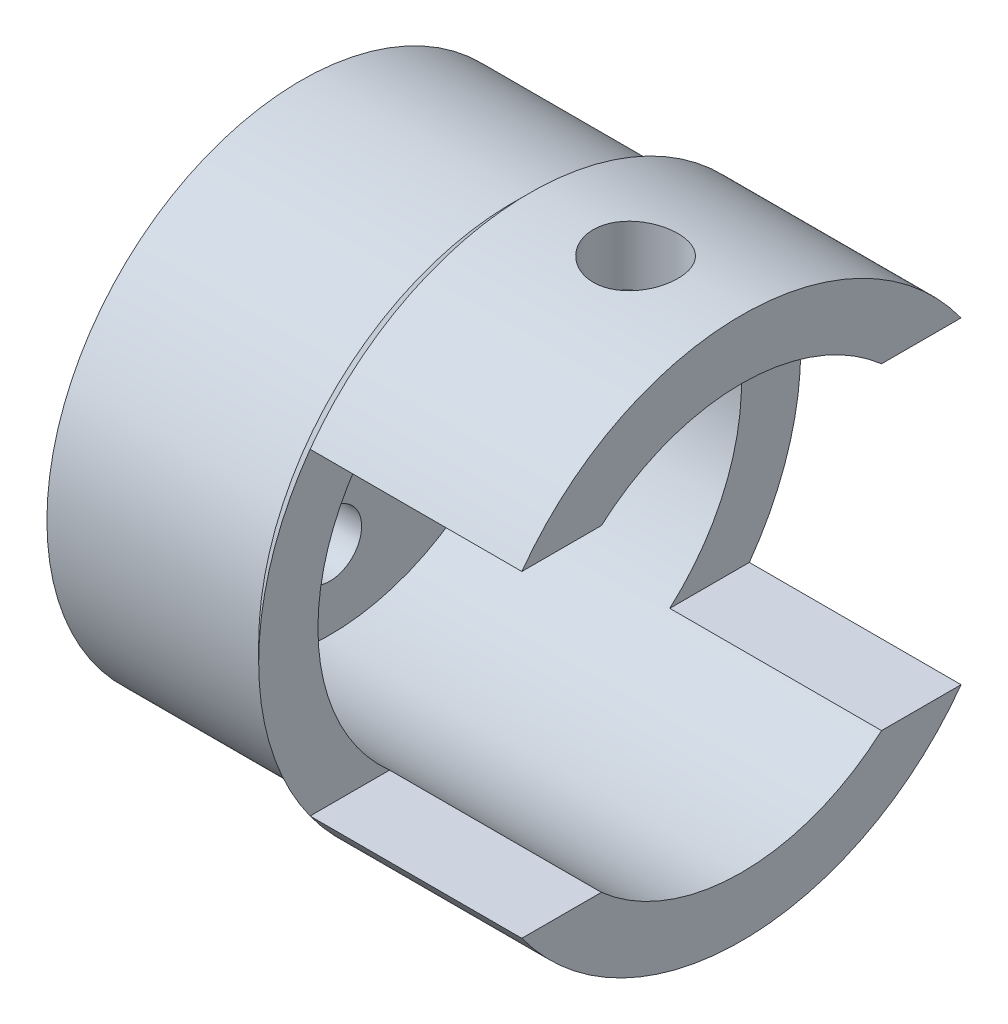
SolidWorks part; units mm, degrees
ref_plane "Plan de face" through (0, 0, 0) normal (0, 0, 1) x (1, 0, 0)
ref_plane "Plan de dessus" through (0, 0, 0) normal (0, 1, 0) x (1, 0, 0)
ref_plane "Plan de droite" through (0, 0, 0) normal (1, 0, 0) x (0, 0, -1)
sketch "Esquisse1" plane through (0, 0, 0) normal (0, 0, 1) x (1, 0, 0)
  line L0 (0, 0) -> (19.5537, 0) construction
  line L1 (0, 12) -> (10, 12)
  line L2 (10, 12) -> (10.7985, 12.7985)
  line L3 (10.7985, 12.7985) -> (20.7985, 12.7985)
  line L7 (0, 12) -> (0, 10)
  line L11 (20.7985, 12.7985) -> (20.7985, 10.7985)
  line L12 (0, 10) -> (0, 0)
  line L13 (0, 0) -> (1.3608, 0)
  line L14 (1.3608, 0) -> (1.3608, 10)
  line L15 (12.2426, 10) -> (1.3608, 10)
  line L16 (12.2426, 10) -> (20.7985, 10)
  line L17 (20.7985, 10) -> (20.7985, 10.7985)
  dimension "D1" = 2
  dimension "D2" = 10
  dimension "D3" = 10
  dimension "D5" = 2
revolve "Révolution1" add sketch "Esquisse1" angle 360 about L0
sketch "Esquisse2" plane through (0, 0, 0) normal (-1, 0, 0) x (0, 0, 1)
  circle A0 centre (0, 0) radius 2.5
  circle A1 centre (0, 6.3) radius 1.5
  circle A2 centre (6.3, 0) radius 1.5
  circle A3 centre (0, -6.3) radius 1.5
  circle A4 centre (-6.3, 0) radius 1.5
  dimension "D1" = 5
  dimension "D2" = 3
  dimension "D3" = 3
  dimension "D4" = 3
  dimension "D5" = 3
  dimension "D6" = 6.3
  dimension "D7" = 6.3
  dimension "D8" = 6.3
  dimension "D9" = 6.3
extrude "Enlèv. mat.-Extru.1" cut sketch "Esquisse2" against normal up to next
sketch "Esquisse3" plane through (0, 0, 0) normal (-1, 0, 0) x (0, 0, 1)
  line L0 (0, -6.3) -> (0, 6.3) construction
ref_plane "Plan1" through (0, 0, 0) normal (0, 0, -1) x (0, 1, 0)
sketch "Esquisse4" plane through (0, 0, 0) normal (0, 0, -1) x (0, 1, 0)
  line L0 (12.7985, 20.7985) -> (-12.7985, 20.7985) construction
  line L1 (7.5015, 20.7985) -> (-7.4985, 20.7985)
  line L2 (7.5015, 20.7985) -> (7.5015, 10.7985)
  line L3 (7.5015, 10.7985) -> (-7.4985, 10.7985)
  line L4 (-7.4985, 20.7985) -> (-7.4985, 10.7985)
  line L5 (12.7985, 10.7985) -> (-12.7985, 10.7985) construction
  line L7 (-12.7985, 20.7985) -> (-12.7985, 10.7985) construction
  dimension "D1" = 15
  dimension "D2" = 5.3
extrude "Enlèv. mat.-Extru.2" cut sketch "Esquisse4" against normal through all both and the other way through all
ref_plane "Plan2" through (0, 12.7985, 0) normal (0, 1, 0) x (1, 0, 0)
sketch "Esquisse5" plane through (0, 12.7985, 0) normal (0, 1, 0) x (1, 0, 0)
  line L0 (20.7985, -10.3696) -> (20.7985, 10.3696) construction
  circle A0 centre (15.7985, 0) radius 2
  dimension "D1" = 4
  dimension "D2" = 5
extrude "Enlèv. mat.-Extru.3" cut sketch "Esquisse5" against normal blind 10 contours A0
